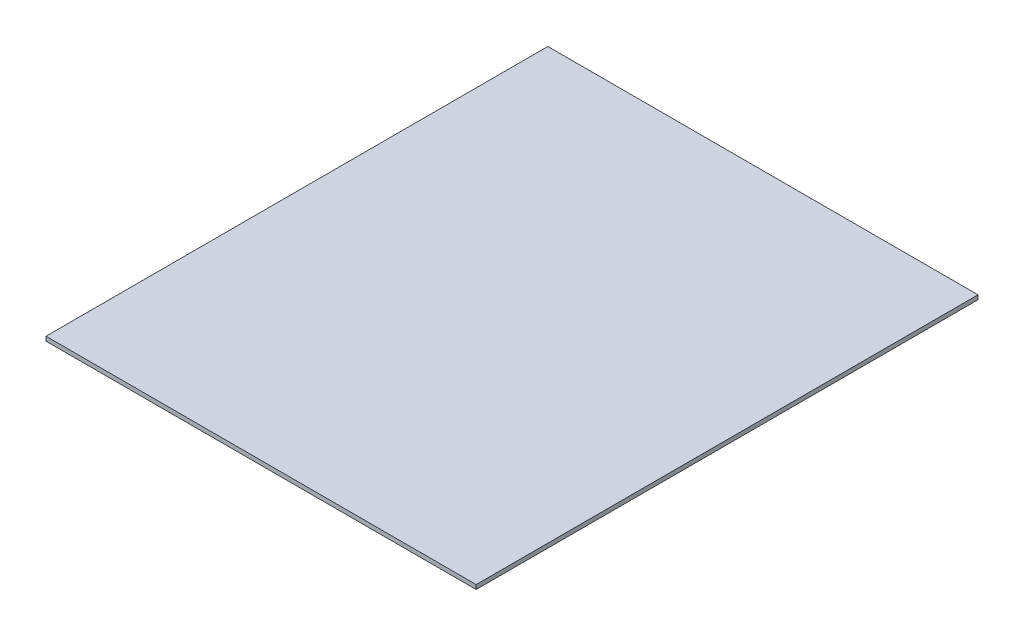
SolidWorks part; units mm, degrees
ref_plane "Front Plane" through (0, 0, 0) normal (0, 0, 1) x (1, 0, 0)
ref_plane "Top Plane" through (0, 0, 0) normal (0, 1, 0) x (1, 0, 0)
ref_plane "Right Plane" through (0, 0, 0) normal (1, 0, 0) x (0, 0, -1)
sketch "Sketch1" plane through (0, 0, 0) normal (0, 1, 0) x (1, 0, 0)
  line L1 (-150, 175) -> (150, 175)
  line L2 (-150, 175) -> (-150, -175)
  line L3 (-150, -175) -> (150, -175)
  line L4 (150, 175) -> (150, -175)
  line L5 (-150, 175) -> (150, -175) construction
  line L6 (-150, -175) -> (150, 175) construction
  point P0 (0, 0)
  dimension "D1" = 300
  dimension "D2" = 350
extrude "Boss-Extrude1" add sketch "Sketch1" along normal blind 3
